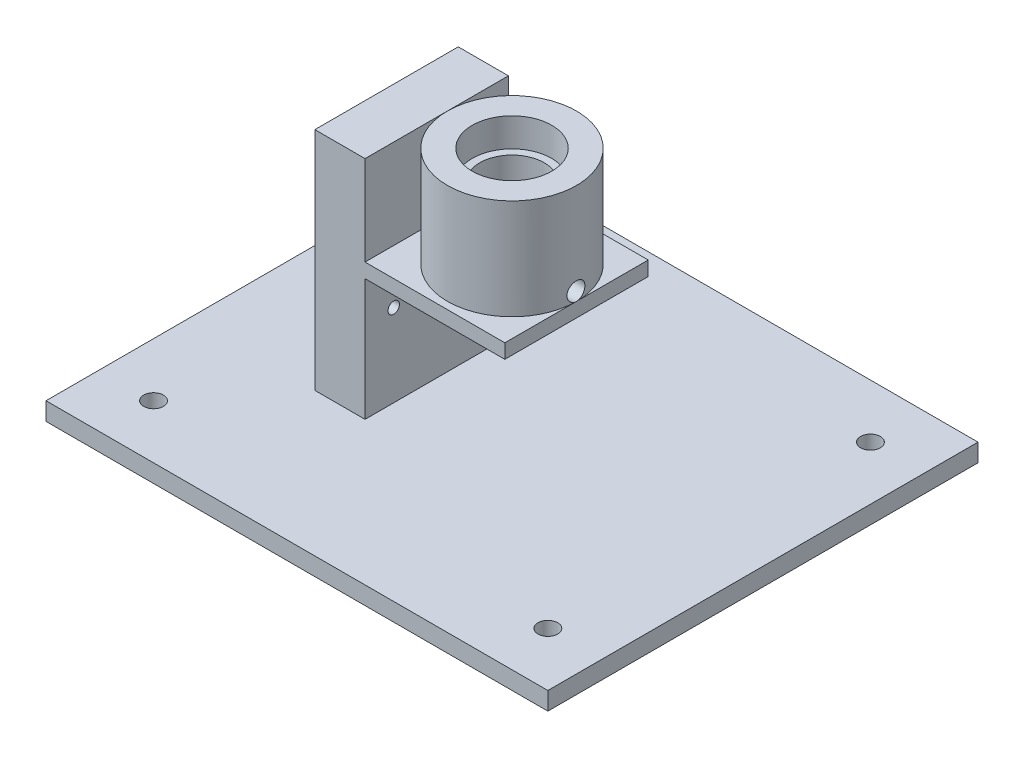
SolidWorks part; units mm, degrees
ref_plane "Front Plane" through (0, 0, 0) normal (0, 0, 1) x (1, 0, 0)
ref_plane "Top Plane" through (0, 0, 0) normal (0, 1, 0) x (1, 0, 0)
ref_plane "Right Plane" through (0, 0, 0) normal (1, 0, 0) x (0, 0, -1)
sketch "Bench_footprint_140x120_profile" plane through (0, 0, 0) normal (0, 1, 0) x (1, 0, 0)
  line L1 (-70, -60) -> (70, -60)
  line L2 (-70, -60) -> (-70, 60)
  line L3 (-70, 60) -> (70, 60)
  line L4 (70, -60) -> (70, 60)
  dimension "D1" = 140
  dimension "D2" = 120
extrude "Bench_footprint_140x120" add sketch "Bench_footprint_140x120_profile" along normal blind 5
sketch "Backbone_profile" plane through (0, 0, 0) normal (0, 0, 1) x (1, 0, 0)
  line L1 (-35, 5) -> (-21, 5)
  line L2 (-35, 5) -> (-35, 68)
  line L3 (-35, 68) -> (-21, 68)
  line L4 (-21, 5) -> (-21, 68)
  dimension "D1" = 14
  dimension "D2" = 63
extrude "Backbone" add sketch "Backbone_profile" along normal blind 40 from offset 20
sketch "Removable_servo_mount_M3_profile" plane through (0, 0, 0) normal (1, 0, 0) x (0, 0, -1)
  circle A0 centre (12, 28) radius 1.6
  circle A1 centre (-12, 28) radius 1.6
  dimension "D1" = 3.2
  dimension "D2" = 3.2
extrude "Removable_servo_mount_M3" cut sketch "Removable_servo_mount_M3_profile" along normal through all from offset 40
sketch "Bearing_bridge_profile" plane through (0, 0, 0) normal (0, 1, 0) x (1, 0, 0)
  line L1 (-35, -20) -> (18, -20)
  line L2 (-35, -20) -> (-35, 20)
  line L3 (-35, 20) -> (18, 20)
  line L4 (18, -20) -> (18, 20)
  dimension "D1" = 53
  dimension "D2" = 40
extrude "Bearing_bridge" add sketch "Bearing_bridge_profile" along normal blind 4 from offset 39
sketch "Bridge_horn_clearance_profile" plane through (0, 0, 0) normal (0, 1, 0) x (1, 0, 0)
  circle A0 centre (0, 0) radius 14
  dimension "D1" = 28
extrude "Bridge_horn_clearance" cut sketch "Bridge_horn_clearance_profile" along normal through all from offset 38
sketch "Drive_collar_chamber_profile" plane through (0, 0, 0) normal (0, 1, 0) x (1, 0, 0)
  circle A0 centre (0, 0) radius 18
  circle A1 centre (0, 0) radius 14
  dimension "D1" = 36
  dimension "D2" = 28
extrude "Drive_collar_chamber" add sketch "Drive_collar_chamber_profile" along normal blind 5 from offset 43
sketch "Bearing_tower_profile" plane through (0, 0, 0) normal (0, 1, 0) x (1, 0, 0)
  circle A0 centre (0, 0) radius 18
  circle A1 centre (0, 0) radius 11.1
  dimension "D1" = 36
  dimension "D2" = 22.2
extrude "Bearing_tower" add sketch "Bearing_tower_profile" along normal blind 23 from offset 48
sketch "Bearing_separation_shoulder_profile" plane through (0, 0, 0) normal (0, 1, 0) x (1, 0, 0)
  circle A0 centre (0, 0) radius 11.1
  circle A1 centre (0, 0) radius 9
  dimension "D1" = 22.2
  dimension "D2" = 18
extrude "Bearing_separation_shoulder" add sketch "Bearing_separation_shoulder_profile" along normal blind 8 from offset 55
sketch "Bench_clamp_holes_profile" plane through (0, 0, 0) normal (0, 1, 0) x (1, 0, 0)
  circle A0 centre (-55, -45) radius 2.75
  circle A1 centre (55, -45) radius 2.75
  circle A2 centre (-55, 45) radius 2.75
  circle A3 centre (55, 45) radius 2.75
  dimension "D1" = 5.5
  dimension "D2" = 5.5
  dimension "D3" = 5.5
  dimension "D4" = 5.5
extrude "Bench_clamp_holes" cut sketch "Bench_clamp_holes_profile" along normal through all from offset 1
sketch "Yaw_crossbolt_access_profile" plane through (0, 0, 0) normal (1, 0, 0) x (0, 0, -1)
  circle A0 centre (0, 45.5) radius 2.5
  dimension "D1" = 5
extrude "Yaw_crossbolt_access" cut sketch "Yaw_crossbolt_access_profile" along normal through all from offset 40
